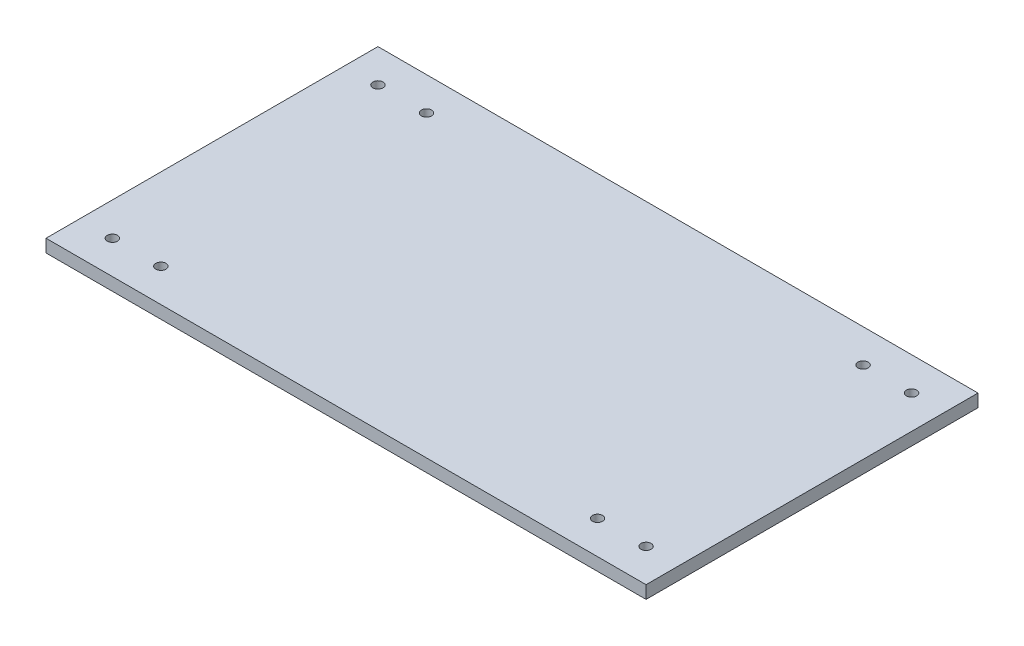
SolidWorks part; units mm, degrees
ref_plane "Front Plane" through (0, 0, 0) normal (0, 0, 1) x (1, 0, 0)
ref_plane "Top Plane" through (0, 0, 0) normal (0, 1, 0) x (1, 0, 0)
ref_plane "Right Plane" through (0, 0, 0) normal (1, 0, 0) x (0, 0, -1)
sketch "Sketch1" plane through (0, 0, 0) normal (0, 1, 0) x (1, 0, 0)
  line L1 (-149.225, -82.55) -> (149.225, -82.55)
  line L2 (-149.225, -82.55) -> (-149.225, 82.55)
  line L3 (-149.225, 82.55) -> (149.225, 82.55)
  line L4 (149.225, -82.55) -> (149.225, 82.55)
  line L5 (-149.225, -82.55) -> (149.225, 82.55) construction
  line L6 (-149.225, 82.55) -> (149.225, -82.55) construction
  point P0 (0, 0)
  dimension "D1" = 298.45
  dimension "D2" = 165.1
extrude "Boss-Extrude1" add sketch "Sketch1" along normal blind 6.35
sketch "Sketch2" plane through (0, 6.35, 0) normal (0, 1, 0) x (1, 0, 0)
  line L1 (-149.225, -82.55) -> (149.225, -82.55) construction
  line L2 (149.225, -82.55) -> (149.225, 82.55) construction
  circle A0 centre (132.715, -66.04) radius 2.54
  circle A1 centre (108.585, -66.04) radius 2.54
  point P8 (0, 0)
  dimension "D1" = 5.08
  dimension "D4" = 5.08
  dimension "D2" = 16.51
  dimension "D3" = 16.51
  dimension "D5" = 24.13
extrude "Cut-Extrude1" cut sketch "Sketch2" against normal up to surface (6.35 mm away) up to face at (0, 0, 0)
sketch "Sketch5" plane through (0, 6.35, 0) normal (0, 1, 0) x (1, 0, 0)
  line L0 (-149.225, 82.55) -> (-149.225, -82.55) construction
  line L1 (-149.225, -82.55) -> (149.225, -82.55) construction
  circle A0 centre (-132.715, -66.04) radius 2.54
  circle A1 centre (-108.585, -66.04) radius 2.54
  point P4 (0, 0)
  dimension "D1" = 5.08
  dimension "D2" = 5.08
  dimension "D3" = 24.13
  dimension "D4" = 16.51
  dimension "D5" = 16.51
extrude "Cut-Extrude2" cut sketch "Sketch5" against normal up to surface (6.35 mm away) up to face at (108.585, 0, 63.5)
sketch "Sketch6" plane through (0, 6.35, 0) normal (0, 1, 0) x (1, 0, 0)
  line L0 (149.225, 82.55) -> (-149.225, 82.55) construction
  line L1 (149.225, -82.55) -> (149.225, 82.55) construction
  circle A0 centre (132.715, 66.04) radius 2.54
  circle A1 centre (108.585, 66.04) radius 2.54
  point P6 (130.5996, 74.3891)
  point P9 (0, 0)
  dimension "D1" = 5.08
  dimension "D2" = 5.08
  dimension "D3" = 24.13
  dimension "D4" = 16.51
  dimension "D5" = 16.51
extrude "Cut-Extrude3" cut sketch "Sketch6" against normal up to surface (6.35 mm away) up to face at (-108.585, 0, 63.5)
sketch "Sketch7" plane through (0, 6.35, 0) normal (0, 1, 0) x (1, 0, 0)
  line L0 (149.225, 82.55) -> (-149.225, 82.55) construction
  line L1 (-149.225, 82.55) -> (-149.225, -82.55) construction
  circle A0 centre (-132.715, 66.04) radius 2.54
  circle A1 centre (-108.585, 66.04) radius 2.54
  point P4 (0, 0)
  point P7 (-132.4591, 68.5585)
  dimension "D1" = 5.08
  dimension "D2" = 5.08
  dimension "D3" = 24.13
  dimension "D4" = 16.51
  dimension "D5" = 16.51
extrude "Cut-Extrude4" cut sketch "Sketch7" against normal up to surface (6.35 mm away) up to face at (108.585, 0, -68.58)
equation "\"base-width\"= \"box-inner-width\" + 2 * \"material-thickness\""
equation "\"box-inner-width\"= 6in"
equation "\"material-thickness\"= 0.25in"
equation "\"converter-cell-inner-length\"= 9in"
equation "\"bus-bar-cell-inner-length\"= 2.5in"
equation "\"base-length\"= \"converter-cell-inner-length\" + \"bus-bar-cell-inner-length\" + \"material-thickness\""
equation "\"D1@Boss-Extrude1\"=\"material-thickness\""
equation "\"D1@Sketch1\"=\"base-length\""
equation "\"D2@Sketch1\"=\"base-width\""
equation "\"screw-bed-length\"= 1.75in"
equation "\"screw-bed-width\"= .75in"
equation "\"mount-hole-radius\"= .2in"
equation "\"mount-hole-center-to-screw-bed-edge\"= .4in"
equation "\"mount-hole-center-to-base-edge\"= \"mount-hole-center-to-screw-bed-edge\" + \"material-thickness\""
equation "\"D1@Sketch2\"=\"mount-hole-radius\""
equation "\"D2@Sketch2\"=\"mount-hole-center-to-base-edge\""
equation "\"D3@Sketch2\"=\"mount-hole-center-to-base-edge\""
equation "\"D4@Sketch2\"=\"mount-hole-radius\""
equation "\"distance-between-mount-hole-centers\"= .95in"
equation "\"D5@Sketch2\"=\"distance-between-mount-hole-centers\""
equation "\"D1@Sketch5\"=\"mount-hole-radius\""
equation "\"D2@Sketch5\"=\"mount-hole-radius\""
equation "\"D3@Sketch5\"=\"distance-between-mount-hole-centers\""
equation "\"D5@Sketch5\"=\"mount-hole-center-to-base-edge\""
equation "\"D1@Sketch6\"=\"mount-hole-radius\""
equation "\"D2@Sketch6\"=\"mount-hole-radius\""
equation "\"D3@Sketch6\"=\"distance-between-mount-hole-centers\""
equation "\"D4@Sketch6\"=\"mount-hole-center-to-base-edge\""
equation "\"D5@Sketch6\"=\"mount-hole-center-to-base-edge\""
equation "\"D1@Sketch7\"=\"mount-hole-radius\""
equation "\"D2@Sketch7\"=\"mount-hole-radius\""
equation "\"D3@Sketch7\"=\"distance-between-mount-hole-centers\""
equation "\"D4@Sketch7\"=\"mount-hole-center-to-base-edge\""
equation "\"D5@Sketch7\"=\"mount-hole-center-to-base-edge\""
